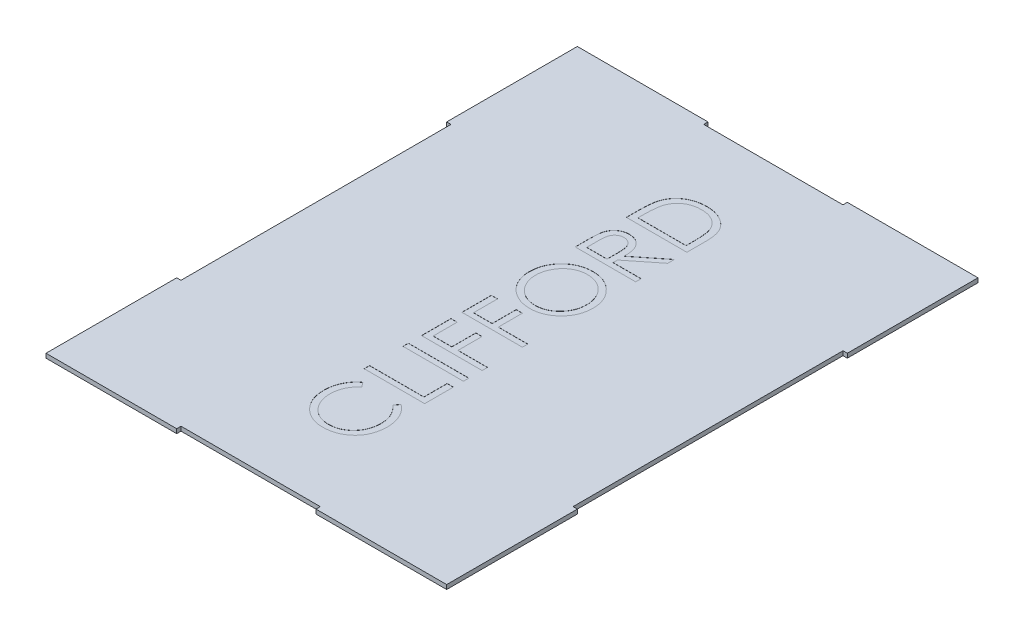
SolidWorks part; units mm, degrees
ref_plane "Alzado" through (0, 0, 0) normal (0, 0, 1) x (1, 0, 0)
ref_plane "Planta" through (0, 0, 0) normal (0, 1, 0) x (1, 0, 0)
ref_plane "Vista lateral" through (0, 0, 0) normal (1, 0, 0) x (0, 0, -1)
sketch "Croquis1" plane through (0, 0, 0) normal (0, 1, 0) x (1, 0, 0)
  line L0 (-53.3, 200) -> (53.3, 200)
  line L1 (-53.3, 200) -> (53.3, 200) construction
  line L2 (-150, 103.3) -> (-150, -103.3) construction
  line L4 (150, 103.3) -> (150, -103.3) construction
  line L7 (-153.3, 203.3) -> (-53.3, 203.3)
  line L8 (-53.3, 200) -> (-53.3, 203.3)
  line L10 (53.3, 200) -> (53.3, 203.3)
  line L11 (53.3, 203.3) -> (150, 203.3)
  line L13 (-150, 103.3) -> (-150, -103.3)
  line L16 (-150, 103.3) -> (-153.3, 103.3)
  line L17 (-153.3, 203.3) -> (-153.3, 103.3)
  line L20 (-150, -103.3) -> (-153.3, -103.3)
  line L21 (-153.3, -200) -> (-153.3, -103.3)
  line L22 (-150, 103.3) -> (-150, -103.3)
  line L23 (-150, 200) -> (-150, 203.3) construction
  line L24 (-150, 200) -> (-153.3, 200) construction
  line L25 (153.3, -103.3) -> (153.3, -200)
  line L26 (150, -200) -> (153.3, -200) construction
  line L27 (153.3, -103.3) -> (150, -103.3)
  line L28 (150, -103.3) -> (150, 103.3)
  line L29 (150, 103.3) -> (153.3, 103.3)
  line L30 (153.3, 103.3) -> (153.3, 203.3)
  line L31 (153.3, 203.3) -> (150, 203.3)
  line L32 (150, 200) -> (150, 203.3) construction
  line L33 (150, 200) -> (153.3, 200) construction
  line L39 (150, -200) -> (150, -203.3) construction
  line L41 (-53.3, -200) -> (53.3, -200)
  line L43 (-153.3, -200) -> (-153.3, -203.3)
  line L44 (-153.3, -203.3) -> (-53.3, -203.3)
  line L45 (-53.3, -200) -> (-53.3, -203.3)
  line L46 (153.3, -200) -> (150, -200)
  line L47 (153.3, -200) -> (153.3, -203.3)
  line L48 (153.3, -203.3) -> (53.3, -203.3)
  line L49 (53.3, -200) -> (53.3, -203.3)
  line L50 (-53.3, -200) -> (53.3, -200) construction
  line L51 (-150, 200) -> (150, 200) construction
  line L52 (-150, 200) -> (-150, -200) construction
  line L53 (-53.3, -200) -> (150, -200) construction
  line L54 (150, 200) -> (150, -200) construction
  line L55 (-150, -200) -> (-53.3, -200) construction
  line L56 (-153.3, -200) -> (-150, -200) construction
  line L57 (-150, -200) -> (-150, -203.3) construction
  point P4 (0, 200)
  point P5 (-150, 0)
  dimension "D1" = 300
  dimension "D2" = 400
  dimension "D3" = 3.3
  dimension "D4" = 100
  dimension "D5" = 100
  dimension "D6" = 100
  dimension "D7" = 100
extrude "Saliente-Extruir1" add sketch "Croquis1" along normal blind 3.3
sketch "Croquis2" plane through (0, 3.3, 0) normal (0, 1, 0) x (1, 0, 0)
  line L0 (25, -150) -> (25, 150) construction
  line L1 (150, -103.3) -> (150, 103.3) construction
  line L2 (25, -150) -> (-25, -150) construction
  line L3 (-25, -150) -> (-25, 150) construction
  line L4 (-25, 150) -> (25, 150) construction
  text T0 "CLIFFORD" font "Century Gothic" height in points 175
  point P4 (25, 0)
  point P5 (0, 0)
  point P6 (0, -150)
  dimension "D1" = 300
  dimension "D2" = 50
extrude "Cortar-Extruir1" cut sketch "Croquis2" against normal blind 0.1
